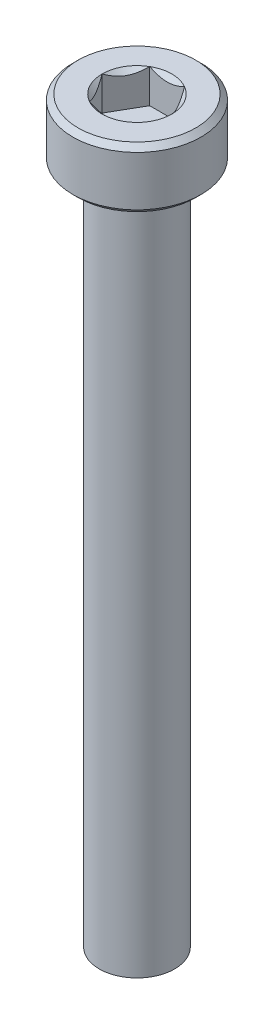
SolidWorks part; units mm, degrees
ref_plane "Front" through (0, 0, 0) normal (0, 0, 1) x (1, 0, 0)
ref_plane "Top" through (0, 0, 0) normal (0, 1, 0) x (1, 0, 0)
ref_plane "Right" through (0, 0, 0) normal (1, 0, 0) x (0, 0, -1)
sketch "Sketch1" plane through (0, 0, 0) normal (0, 1, 0) x (1, 0, 0)
  circle A0 centre (0, 0) radius 4.25
  dimension "D1" = 8.5
extrude "Boss-Extrude1" add sketch "Sketch1" along normal blind 4
sketch "Sketch2" plane through (0, 4, 0) normal (0, 1, 0) x (1, 0, 0)
  line L1 (1.1547, 2) -> (-1.1547, 2)
  line L2 (-1.1547, 2) -> (-2.3094, 0)
  line L3 (-2.3094, 0) -> (-1.1547, -2)
  line L4 (-1.1547, -2) -> (1.1547, -2)
  line L5 (1.1547, -2) -> (2.3094, 0)
  line L6 (2.3094, 0) -> (1.1547, 2)
  circle A0 centre (0, 0) radius 2 construction
  point P10 (0, 2)
  dimension "D1" = 4
extrude "Cut-Extrude1" cut sketch "Sketch2" against normal blind 2.25
sketch "Sketch3" plane through (0, 4, 0) normal (0, 1, 0) x (1, 0, 0)
  circle A0 centre (0, 0) radius 2.3094
extrude "Cut-Extrude2" cut sketch "Sketch3" against normal through all draft 45
chamfer "Chamfer1" distance 0.35 angle 45 2 edges at (0, 0, 4.25) (0, 4, 4.25)
sketch "草图1" plane through (0, 0, 0) normal (0, -1, 0) x (-1, 0, 0)
  circle A0 centre (0, 0) radius 2.5
  dimension "D1" = 5
extrude "凸台-拉伸1" add sketch "草图1" along normal blind 45
